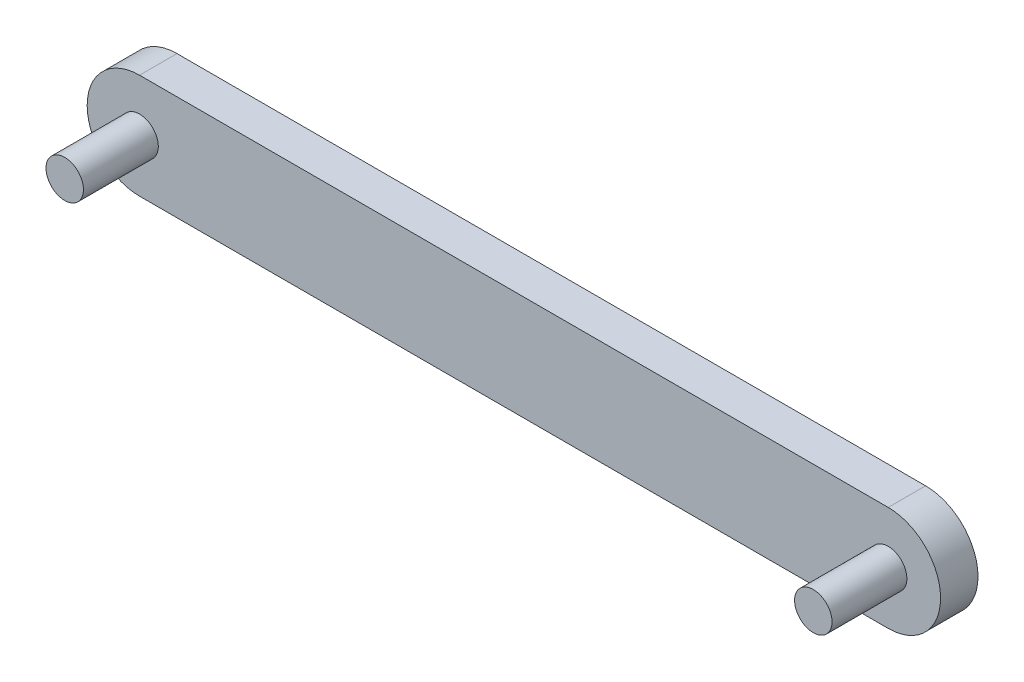
SolidWorks part; units mm, degrees
ref_plane "Front Plane" through (0, 0, 0) normal (0, 0, 1) x (1, 0, 0)
ref_plane "Top Plane" through (0, 0, 0) normal (0, 1, 0) x (1, 0, 0)
ref_plane "Right Plane" through (0, 0, 0) normal (1, 0, 0) x (0, 0, -1)
sketch "Sketch1" plane through (0, 0, 0) normal (0, 0, 1) x (1, 0, 0)
  line L1 (-50, -7) -> (50, -7)
  line L3 (-50, 7) -> (50, 7)
  line L5 (-50, -7) -> (50, 7) construction
  line L6 (-50, 7) -> (50, -7) construction
  arc A0 (-50, 7) -> (-50, -7) centre (-50, 0) ccw
  arc A1 (50, 7) -> (50, -7) centre (50, 0) cw
  point P0 (0, 0)
  dimension "D1" = 7
  dimension "D2" = 7
  dimension "D3" = 100
extrude "Boss-Extrude1" add sketch "Sketch1" along normal blind 5
sketch "Sketch2" plane through (0, 0, 5) normal (0, 0, 1) x (1, 0, 0)
  line L0 (0, 0) -> (0, 16.7636) construction
  circle A0 centre (-50, 0) radius 2.5
  arc A1 (-50, 7) -> (-50, -7) centre (-50, 0) ccw construction
  circle A2 centre (50, 0) radius 2.5
  dimension "D1" = 5
extrude "Boss-Extrude2" add sketch "Sketch2" along normal blind 10
